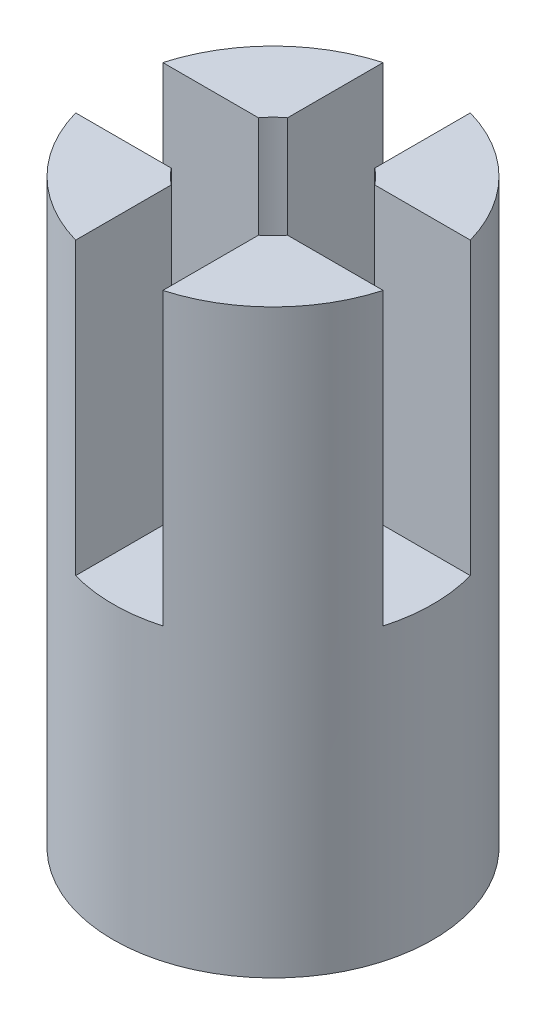
SolidWorks part; units mm, degrees
ref_plane "Plan de face" through (0, 0, 0) normal (0, 0, 1) x (1, 0, 0)
ref_plane "Plan de dessus" through (0, 0, 0) normal (0, 1, 0) x (1, 0, 0)
ref_plane "Plan de droite" through (0, 0, 0) normal (1, 0, 0) x (0, 0, -1)
sketch "Esquisse1" plane through (0, 0, 0) normal (0, 1, 0) x (1, 0, 0)
  circle A0 centre (0, 0) radius 2.5
  circle A1 centre (0, 0) radius 5.5
  dimension "D1" = 5
  dimension "D2" = 3
extrude "Boss.-Extru.1" add sketch "Esquisse1" along normal blind 20
sketch "Esquisse2" plane through (0, 20, 0) normal (0, 1, 0) x (1, 0, 0)
  line L0 (-1.5, 5.8067) -> (-1.5, 1.5)
  line L1 (1.5, -5.7921) -> (1.5, -1.5)
  line L2 (-1.5, 5.8067) -> (1.5, 5.8067)
  line L3 (-1.5, -5.7921) -> (1.5, -5.7921)
  line L4 (-8.8086, 1.5) -> (-1.5, 1.5)
  line L5 (-9.1884, -1.5) -> (-1.5, -1.5)
  line L6 (-8.8086, 1.5) -> (-9.1884, -1.5)
  line L7 (7.9813, 1.5) -> (7.7836, -1.5)
  line L8 (-1.5, -1.5) -> (-1.5, -5.7921)
  line L9 (1.5, 1.5) -> (1.5, 5.8067)
  line L10 (1.5, -1.5) -> (7.7836, -1.5)
  line L11 (1.5, 1.5) -> (7.9813, 1.5)
  dimension "D1" = 1.5
  dimension "D2" = 1.5
  dimension "D3" = 1.5
  dimension "D4" = 1.5
extrude "Enlèv. mat.-Extru.1" cut sketch "Esquisse2" against normal blind 10
